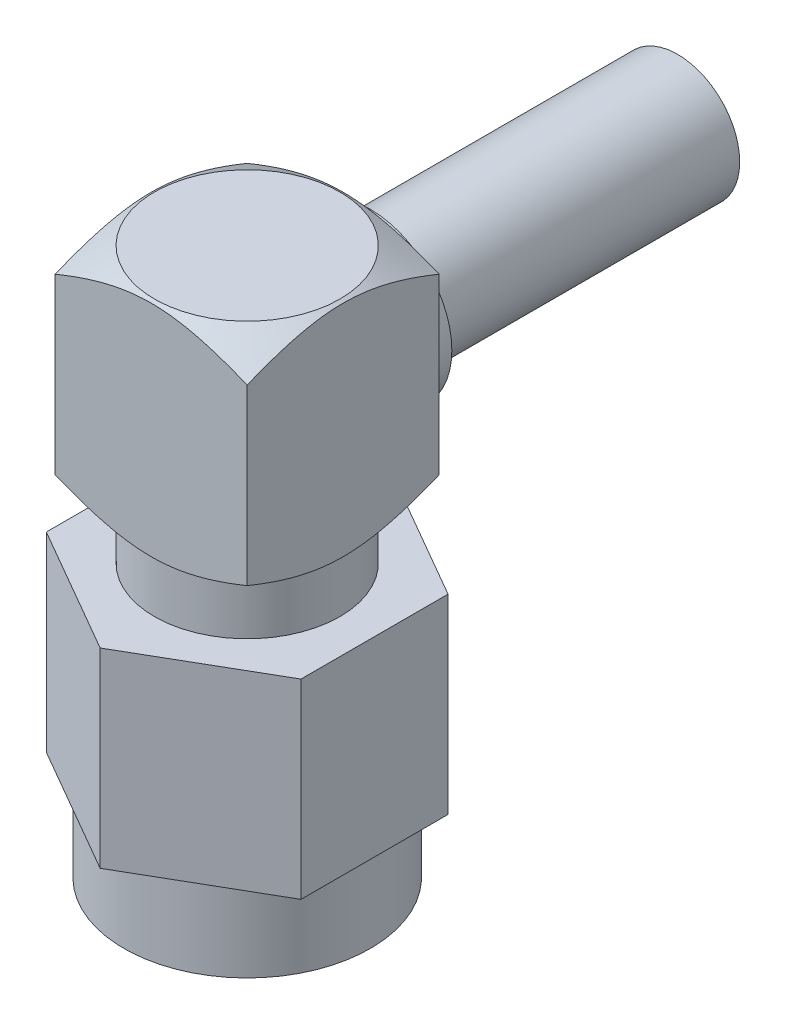
SolidWorks part; units mm, degrees
ref_plane "Front Plane" through (0, 0, 0) normal (0, 0, 1) x (1, 0, 0)
ref_plane "Top Plane" through (0, 0, 0) normal (0, 1, 0) x (1, 0, 0)
ref_plane "Right Plane" through (0, 0, 0) normal (1, 0, 0) x (0, 0, -1)
sketch "Sketch1" plane through (0, 0, 0) normal (0, 1, 0) x (1, 0, 0)
  line L1 (-2.9972, -2.9972) -> (2.9972, -2.9972)
  line L2 (-2.9972, -2.9972) -> (-2.9972, 2.9972)
  line L3 (-2.9972, 2.9972) -> (2.9972, 2.9972)
  line L4 (2.9972, -2.9972) -> (2.9972, 2.9972)
  line L5 (-2.9972, -2.9972) -> (2.9972, 2.9972) construction
  line L6 (-2.9972, 2.9972) -> (2.9972, -2.9972) construction
  point P0 (0, 0)
  dimension "D1" = 5.9944
  dimension "D2" = 5.9944
extrude "Boss-Extrude1" add sketch "Sketch1" along normal blind 8.5852
sketch "Sketch2" plane through (0, 0, 0) normal (0, 0, 1) x (1, 0, 0)
  line L0 (-2.9972, 0) -> (2.9972, 0) construction
  line L1 (-2.8956, 1.6129) -> (2.8956, 1.6129)
  line L2 (-2.8956, 1.6129) -> (-2.8956, 0)
  line L3 (-2.8956, 0) -> (2.8956, 0)
  line L4 (2.8956, 1.6129) -> (2.8956, 0)
  line L5 (-2.8956, 1.6129) -> (2.8956, 0) construction
  line L6 (-2.8956, 0) -> (2.8956, 1.6129) construction
  line L7 (2.8956, 1.6129) -> (5.4609, 3.094)
  line L8 (5.4609, 3.094) -> (5.4609, -1.4811)
  line L9 (2.8956, 0) -> (5.4609, -1.4811)
  line L10 (0, 0.8065) -> (6.3357, 0.8065) construction
  line L11 (0, 0.8065) -> (0, 6.5009) construction
  line L16 (2.8956, 1.6129) -> (2.8956, 8.5852)
  line L17 (-2.9972, 8.5852) -> (2.9972, 8.5852) construction
  line L18 (-2.9972, 8.5852) -> (2.9972, 8.5852)
  line L19 (2.8956, 8.5852) -> (5.4609, 7.1041)
  line L20 (5.4609, 7.1041) -> (5.4609, 8.5852)
  line L21 (5.4609, 8.5852) -> (2.9972, 8.5852)
  point P0 (0, 0.8065)
  point P14 (5.4609, 0.8065)
  dimension "D1" = 5.7912
  dimension "D2" = 1.6129
  dimension "D3" = 0
  dimension "D4" = 30
  dimension "D5" = 30
revolve "Cut-Revolve1" cut sketch "Sketch2" angle 360 about L11
sketch "Sketch3" plane through (0, 0, -2.9972) normal (0, 0, -1) x (-1, 0, 0)
  circle A0 centre (0, 5.0991) radius 2.54
extrude "Boss-Extrude2" add sketch "Sketch3" along normal blind 0.8509
sketch "Sketch4" plane through (0, 0, -3.8481) normal (0, 0, -1) x (-1, 0, 0)
  circle A0 centre (0, 5.0991) radius 1.9367
extrude "Boss-Extrude3" add sketch "Sketch4" along normal blind 9.5885
sketch "Sketch5" plane through (0, 0, 0) normal (0, -1, 0) x (-1, 0, 0)
  line L1 (0, 4.5901) -> (-3.9751, 2.295)
  line L2 (-3.9751, 2.295) -> (-3.9751, -2.295)
  line L3 (-3.9751, -2.295) -> (0, -4.5901)
  line L4 (0, -4.5901) -> (3.9751, -2.295)
  line L5 (3.9751, -2.295) -> (3.9751, 2.295)
  line L6 (3.9751, 2.295) -> (0, 4.5901)
  circle A0 centre (0, 0) radius 3.9751 construction
  dimension "D1" = 7.9502
extrude "Boss-Extrude4" add sketch "Sketch5" along normal blind 5.9563
sketch "Sketch6" plane through (0, -5.9563, 0) normal (0, -1, 0) x (-1, 0, 0)
  circle A0 centre (0, 0) radius 3.8481
extrude "Boss-Extrude5" add sketch "Sketch6" along normal blind 2.54
sketch "Sketch7" plane through (0, -8.4963, 0) normal (0, -1, 0) x (-1, 0, 0)
  circle A0 centre (0, 0) radius 3.2512
extrude "Cut-Extrude1" cut sketch "Sketch7" against normal blind 2.54
